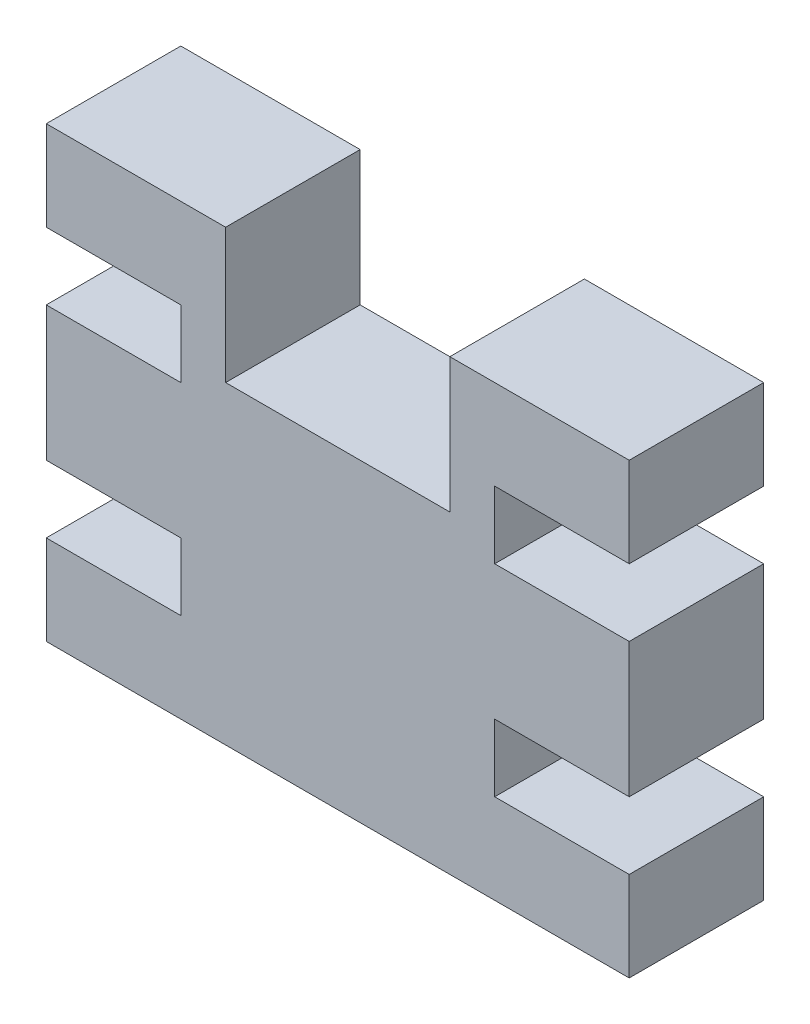
SolidWorks part; units mm, degrees
ref_plane "Plan de face" through (0, 0, 0) normal (0, 0, 1) x (1, 0, 0)
ref_plane "Plan de dessus" through (0, 0, 0) normal (0, 1, 0) x (1, 0, 0)
ref_plane "Plan de droite" through (0, 0, 0) normal (1, 0, 0) x (0, 0, -1)
sketch "Sketch1" plane through (0, 0, 0) normal (0, 0, 1) x (1, 0, 0)
  line L1 (6.5, 4.6335) -> (-6.5, 4.6335)
  line L2 (6.5, 4.6335) -> (6.5, 14.6335)
  line L3 (6.5, 14.6335) -> (-6.5, 14.6335)
  line L4 (-6.5, 4.6335) -> (-6.5, 14.6335)
  line L5 (6.5, 4.6335) -> (-6.5, 14.6335) construction
  line L6 (6.5, 14.6335) -> (-6.5, 4.6335) construction
  point P0 (0, 9.6335)
  dimension "D1" = 13
  dimension "D2" = 10
extrude "Boss-Extrude1" add sketch "Sketch1" along normal blind 3
sketch "Sketch2" plane through (0, 0, 3) normal (0, 0, 1) x (1, 0, 0)
  line L0 (-6.5, 14.6335) -> (-6.5, 4.6335) construction
  line L1 (-6.5, 12.6335) -> (-3.5, 12.6335)
  line L2 (-6.5, 12.6335) -> (-6.5, 11.1335)
  line L3 (-6.5, 11.1335) -> (-3.5, 11.1335)
  line L4 (-3.5, 12.6335) -> (-3.5, 11.1335)
  line L5 (6.5, 14.6335) -> (-6.5, 14.6335) construction
  line L7 (-6.5, 8.1335) -> (-3.5, 8.1335)
  line L8 (-6.5, 8.1335) -> (-6.5, 6.6335)
  line L9 (-6.5, 6.6335) -> (-3.5, 6.6335)
  line L10 (-3.5, 8.1335) -> (-3.5, 6.6335)
  dimension "D1" = 2
  dimension "D2" = 3
  dimension "D3" = 1.5
  dimension "D4" = 1.5
  dimension "D5" = 3
  dimension "D6" = 3
extrude "Cut-Extrude1" cut sketch "Sketch2" against normal blind 3
sketch "Sketch3" plane through (0, 0, 3) normal (0, 0, 1) x (1, 0, 0)
  line L0 (6.5, 4.6335) -> (6.5, 14.6335) construction
  line L1 (6.5, 12.6335) -> (3.5, 12.6335)
  line L2 (6.5, 12.6335) -> (6.5, 11.1335)
  line L3 (6.5, 11.1335) -> (3.5, 11.1335)
  line L4 (3.5, 12.6335) -> (3.5, 11.1335)
  line L5 (6.5, 14.6335) -> (-6.5, 14.6335) construction
  line L7 (6.5, 8.1335) -> (3.5, 8.1335)
  line L8 (6.5, 8.1335) -> (6.5, 6.6335)
  line L9 (6.5, 6.6335) -> (3.5, 6.6335)
  line L10 (3.5, 8.1335) -> (3.5, 6.6335)
  dimension "D1" = 3
  dimension "D2" = 1.5
  dimension "D3" = 2
  dimension "D4" = 3
  dimension "D5" = 1.5
  dimension "D6" = 3
extrude "Cut-Extrude2" cut sketch "Sketch3" against normal blind 3
sketch "Sketch5" plane through (0, 0, 3) normal (0, 0, 1) x (1, 0, 0)
  line L0 (6.5, 14.6335) -> (-6.5, 14.6335) construction
  line L1 (-2.5, 14.6335) -> (2.5, 14.6335)
  line L2 (-2.5, 14.6335) -> (-2.5, 11.6335)
  line L3 (-2.5, 11.6335) -> (2.5, 11.6335)
  line L4 (2.5, 14.6335) -> (2.5, 11.6335)
  line L5 (-6.5, 14.6335) -> (-6.5, 12.6335) construction
  dimension "D1" = 4
  dimension "D2" = 5
  dimension "D3" = 3
extrude "Cut-Extrude6" cut sketch "Sketch5" against normal blind 3
